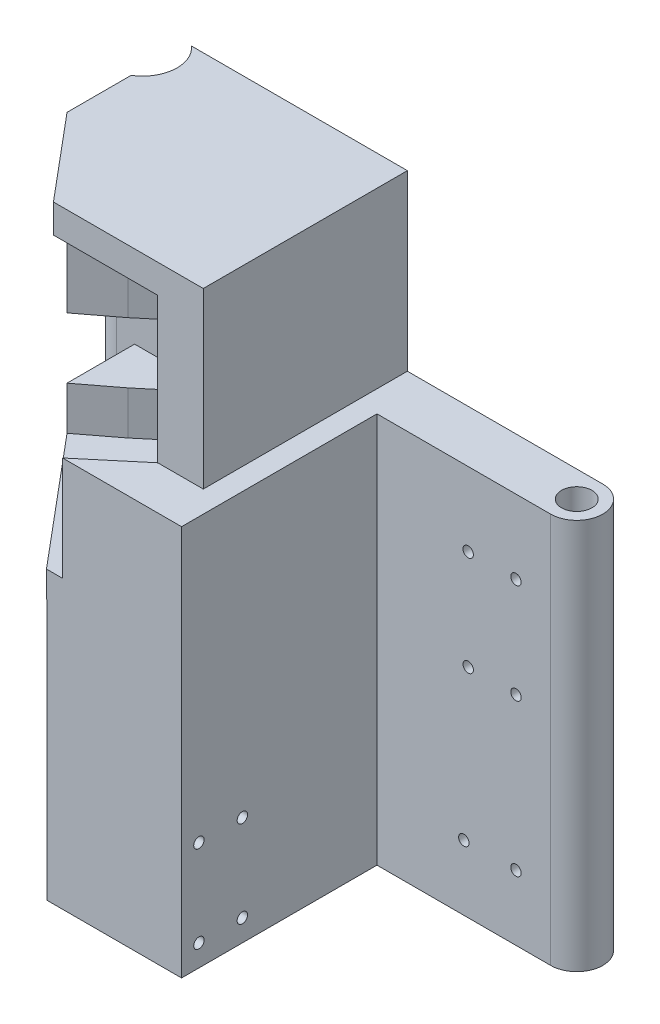
SolidWorks part; units mm, degrees
ref_plane "Front Plane" through (0, 0, 0) normal (0, 0, 1) x (1, 0, 0)
ref_plane "Top Plane" through (0, 0, 0) normal (0, 1, 0) x (1, 0, 0)
ref_plane "Right Plane" through (0, 0, 0) normal (1, 0, 0) x (0, 0, -1)
sketch "Sketch1" plane through (0, 0, 0) normal (0, 1, 0) x (1, 0, 0)
  line L0 (0, 7.62) -> (127, 7.62)
  line L1 (0, -7.62) -> (69.85, -7.62)
  line L2 (76.2, -7.62) -> (76.2, -64.77)
  line L3 (69.85, -7.62) -> (69.85, -64.77)
  line L4 (69.85, -64.77) -> (76.2, -64.77)
  line L5 (76.2, -7.62) -> (127, -7.62)
  circle A0 centre (0, 0) radius 4.445
  arc A1 (0, 7.62) -> (0, -7.62) centre (0, 0) ccw
  arc A2 (127, -7.62) -> (127, 7.62) centre (127, 0) ccw
  circle A3 centre (127, 0) radius 4.445
  dimension "D1" = 15.24
  dimension "D2" = 8.89
  dimension "D4" = 57.15
  dimension "D5" = 50.8
  dimension "D6" = 6.35
  dimension "D3" = 2
extrude "Boss-Extrude1" add sketch "Sketch1" along normal blind 114.3
sketch "Sketch5" plane through (76.2, 0, 0) normal (1, 0, 0) x (0, 0, -1)
sketch "Sketch12" plane through (0, 114.3, 0) normal (0, 1, 0) x (1, 0, 0)
  line L0 (69.85, -7.62) -> (69.85, -64.77)
  line L1 (69.85, -7.62) -> (69.85, -64.77) construction
  line L2 (69.85, -64.77) -> (21.8955, -7.62)
  line L3 (0, -7.62) -> (69.85, -7.62) construction
  line L4 (21.8955, -7.62) -> (69.85, -7.62)
  dimension "D1" = 40
  dimension "D2" = 57.15
extrude "Boss-Extrude3" add sketch "Sketch12" against normal blind 38.1
sketch "Sketch13" plane through (0, 114.3, 0) normal (0, 1, 0) x (1, 0, 0)
  line L0 (127, 7.62) -> (0, 7.62) construction
  line L1 (21.8955, -7.62) -> (69.85, -7.62)
  line L2 (21.8955, -7.62) -> (21.8955, 7.62)
  line L3 (21.8955, 7.62) -> (69.85, 7.62)
  line L4 (69.85, -7.62) -> (69.85, 7.62)
  line L5 (69.85, -7.62) -> (69.85, -64.77)
  line L6 (69.85, -64.77) -> (21.8955, -8.1167)
  line M7 (21.8955, -7.62) -> (69.85, -64.77)
  line M12 (127, 7.62) -> (0, 7.62)
  dimension "D1" = 90
extrude "Boss-Extrude4" add sketch "Sketch13" along normal blind 50.8 contours L1 L4 L2 M12 | L5 L1 M7
sketch "Sketch14" plane through (0, 76.2, 0) normal (0, -1, 0) x (1, 0, 0)
  line L0 (21.8955, 7.62) -> (69.85, 64.77)
  line L2 (12.1667, 15.7834) -> (53.2713, 64.77)
  line L3 (12.1667, 15.7834) -> (5.3168, 7.62)
  line L4 (0, 7.62) -> (69.85, 7.62) construction
  line L5 (69.85, 64.77) -> (53.2713, 64.77)
  line L6 (21.8955, 7.62) -> (5.3168, 7.62)
  line L7 (12.1667, 15.7834) -> (60.1212, 72.9334) construction
  dimension "D1" = 12.7
extrude "Boss-Extrude5" add sketch "Sketch14" against normal blind 7.62
sketch "Sketch15" plane through (0, 165.1, 0) normal (0, 1, 0) x (1, 0, 0)
  line L0 (69.85, -64.77) -> (53.2713, -64.77)
  line L1 (53.2713, -64.77) -> (5.3168, -7.62)
  line L2 (5.3168, -7.62) -> (5.3168, 7.62)
  line L3 (21.8955, 7.62) -> (0, 7.62) construction
  line L4 (5.3168, 7.62) -> (21.8955, 7.62)
  line L5 (21.8955, 7.62) -> (21.8955, -7.62)
  line L6 (21.8955, -7.62) -> (69.85, -64.77)
extrude "Boss-Extrude6" add sketch "Sketch15" against normal blind 8.382
sketch "Sketch17" plane through (0, 156.718, 0) normal (0, -1, 0) x (1, 0, 0)
  line L1 (5.3168, 7.62) -> (53.2713, 64.77) construction
  line L2 (12.1667, 15.7834) -> (5.3168, 7.62)
  line L3 (5.3168, 7.62) -> (5.3168, -7.62)
  line L4 (5.3168, -7.62) -> (21.8955, -7.62)
  line L5 (21.8955, -7.62) -> (21.8955, 7.62)
  line L6 (25.1608, 11.5115) -> (15.4321, 19.6749)
  line L7 (15.4321, 19.6749) -> (12.1667, 15.7834)
  line L8 (25.1608, 11.5115) -> (21.8955, 7.62)
  dimension "D1" = 5.08
extrude "Boss-Extrude7" add sketch "Sketch17" along normal blind 76.2
sketch "Sketch18" plane through (0, 76.2, 0) normal (0, -1, 0) x (1, 0, 0)
  line L0 (5.3168, 7.62) -> (5.3168, 27.3777)
  line L1 (5.3168, 7.62) -> (53.2713, 64.77)
  line L2 (5.3168, 27.3777) -> (36.6927, 64.77)
  line L3 (53.2713, 64.77) -> (36.6927, 64.77)
  line L5 (-4.412, 15.7834) -> (43.5426, 72.9334) construction
  dimension "D1" = 12.7
extrude "Boss-Extrude8" add sketch "Sketch18" against normal blind 7.62
sketch "Sketch19" plane through (0, 165.1, 0) normal (0, 1, 0) x (1, 0, 0)
  line L0 (5.3168, -7.62) -> (5.3168, -27.3777)
  line L1 (5.3168, -27.3777) -> (36.6927, -64.77)
  line L2 (36.6927, -64.77) -> (53.2713, -64.77)
  line L3 (69.85, -64.77) -> (36.6927, -64.77) construction
  line L4 (53.2713, -64.77) -> (5.3168, -7.62)
extrude "Boss-Extrude9" add sketch "Sketch19" against normal blind 8.382
sketch "Sketch20" plane through (0, 156.718, 0) normal (0, -1, 0) x (1, 0, 0)
  line L0 (15.4321, 19.6749) -> (5.3168, 27.3777)
  line L1 (5.3168, 27.3777) -> (5.3168, 7.62)
  line L2 (5.3168, 7.62) -> (15.4321, 19.6749)
extrude "Boss-Extrude10" add sketch "Sketch20" along normal blind 73.66
sketch "Sketch22" plane through (0, 156.718, 0) normal (0, -1, 0) x (1, 0, 0)
  line L0 (69.85, 64.77) -> (58.0947, 50.7606)
  line L1 (69.85, 64.77) -> (25.1608, 11.5115) construction
  line L2 (58.0947, 50.7606) -> (41.3989, 64.77)
  line L3 (36.6927, 64.77) -> (69.85, 64.77) construction
  line L4 (41.3989, 64.77) -> (69.85, 64.77)
  dimension "D1" = 18.288
extrude "Boss-Extrude11" add sketch "Sketch22" along normal blind 73.406
sketch "Sketch23" plane through (5.3168, 0, 0) normal (-1, 0, 0) x (0, 0, 1)
  line L5 (27.3777, 83.82) -> (27.3777, 156.718) construction
  line L6 (27.3777, 96.52) -> (7.62, 96.52)
  line L7 (27.3777, 96.52) -> (27.3777, 114.3)
  line L8 (27.3777, 114.3) -> (7.62, 114.3)
  line L9 (7.62, 96.52) -> (7.62, 114.3)
  line L10 (7.62, 114.3) -> (7.62, 76.2) construction
  dimension "D1" = 12.7
  dimension "D2" = 17.78
extrude "Cut-Extrude11" cut sketch "Sketch23" against normal blind 20.32
sketch "Sketch24" plane through (0, 165.1, 0) normal (0, 1, 0) x (1, 0, 0)
  circle A0 centre (0, 0) radius 10.16
  dimension "D1" = 20.32
extrude "Cut-Extrude12" cut sketch "Sketch24" against normal up to surface (50.8 mm away) up to face at (0, 114.3, 4.445)
sketch "Sketch25" plane through (0, 0, 64.77) normal (0, 0, 1) x (1, 0, 0)
  line L0 (5.3168, 156.718) -> (36.6927, 156.718) construction
  line L1 (69.85, 114.3) -> (36.6927, 114.3)
  line L2 (69.85, 114.3) -> (69.85, 165.1)
  line L3 (69.85, 165.1) -> (36.6927, 165.1)
  line L4 (36.6927, 114.3) -> (36.6927, 165.1)
  line L5 (36.6927, 165.1) -> (12.9618, 165.1)
  line L6 (36.6927, 165.1) -> (36.6927, 156.718)
  line L7 (36.6927, 156.718) -> (12.9618, 156.718)
  line L8 (12.9618, 165.1) -> (12.9618, 156.718)
  line M1 (41.3989, 156.718) -> (41.3989, 83.82)
  line M9 (69.85, 114.3) -> (69.85, 165.1)
  line M10 (69.85, 165.1) -> (36.6927, 165.1)
  line M11 (36.6927, 165.1) -> (36.6927, 156.718)
  line M12 (36.6927, 156.718) -> (41.3989, 156.718)
extrude "Cut-Extrude14" cut sketch "Sketch25" against normal blind 12.7 contours L1 M9 M10 M11 M12 M1 | L5 L8 L7 M11
sketch "Sketch26" plane through (0, 0, 7.62) normal (0, 0, 1) x (1, 0, 0)
  line L0 (69.85, 76.2) -> (5.3168, 76.2) construction
  line L1 (69.85, 0) -> (36.83, 0)
  line L2 (69.85, 0) -> (69.85, 76.2)
  line L3 (69.85, 76.2) -> (36.83, 76.2)
  line L4 (36.83, 0) -> (36.83, 76.2)
  dimension "D1" = 33.02
extrude "Boss-Extrude13" add sketch "Sketch26" along normal up to surface (57.15 mm away) up to face at (56.0354, 68.58, 64.77)
sketch "Sketch34" plane through (0, 0, -7.62) normal (0, 0, -1) x (-1, 0, 0)
  line L0 (-127, 114.3) -> (-69.85, 114.3) construction
  line L1 (-127, 114.3) -> (-127, 0) construction
  circle A0 centre (-109.22, 95.25) radius 1.524
  circle A1 centre (-95.25, 95.25) radius 1.524
  circle A2 centre (-95.25, 63.5) radius 1.524
  circle A3 centre (-109.22, 63.5) radius 1.524
  circle A10 centre (-109.22, 44.45) radius 1.524
  circle A11 centre (-95.25, 44.45) radius 1.524
  circle A12 centre (-109.22, 12.7) radius 1.524
  circle A13 centre (-95.25, 12.7) radius 1.524
  dimension "D1" = 3.048
  dimension "D2" = 2
  dimension "D5" = 13.97
  dimension "D6" = 31.75
  dimension "D7" = 13.97
  dimension "D8" = 19.05
  dimension "D9" = 17.78
extrude "Cut-Extrude18" cut sketch "Sketch34" against normal blind 5.08
sketch "Sketch35" plane through (0, 0, 7.62) normal (0, 0, 1) x (1, 0, 0)
  line L0 (127, 114.3) -> (127, 0) construction
  circle A4 centre (102.87, 92.71) radius 1.524
  circle A5 centre (116.84, 92.71) radius 1.524
  circle A6 centre (102.87, 63.5) radius 1.524
  circle A7 centre (116.84, 63.5) radius 1.524
  circle A8 centre (101.6, 19.05) radius 1.524
  circle A9 centre (116.84, 19.05) radius 1.524
  dimension "D1" = 3.048
  dimension "D2" = 3.048
  dimension "D3" = 44.45
  dimension "D4" = 1.27
  dimension "D5" = 29.21
  dimension "D6" = 13.97
  dimension "D7" = 13.97
  dimension "D8" = 10.16
  dimension "D9" = 2
extrude "Cut-Extrude19" cut sketch "Sketch35" against normal blind 5.08
sketch "Sketch36" plane through (76.2, 0, 0) normal (1, 0, 0) x (0, 0, -1)
  line L0 (-64.77, 114.3) -> (-64.77, 0) construction
  line L1 (-64.77, 0) -> (-7.62, 0) construction
  circle A0 centre (-59.69, 6.35) radius 1.524
  circle A1 centre (-46.99, 6.35) radius 1.524
  circle A2 centre (-46.99, 31.75) radius 1.524
  circle A3 centre (-59.69, 31.75) radius 1.524
  dimension "D1" = 3.048
  dimension "D2" = 5.08
  dimension "D3" = 6.35
extrude "Cut-Extrude20" cut sketch "Sketch36" against normal blind 5.08
sketch "Sketch37" plane through (0, 0, 0) normal (0, -1, 0) x (1, 0, 0)
  line L0 (0, 7.62) -> (36.83, 7.62) construction
  line L1 (46.99, 41.91) -> (68.58, 41.91)
  line L2 (46.99, 41.91) -> (46.99, 7.62)
  line L3 (46.99, 7.62) -> (68.58, 7.62)
  line L4 (68.58, 41.91) -> (68.58, 7.62)
  line L5 (76.2, 64.77) -> (76.2, 7.62) construction
  dimension "D1" = 21.59
  dimension "D2" = 34.29
  dimension "D3" = 7.62
extrude "Cut-Extrude21" cut sketch "Sketch37" against normal blind 50.8
sketch "Sketch38" plane through (0, 0, 0) normal (0, -1, 0) x (1, 0, 0)
  circle A0 centre (57.785, 48.26) radius 1.524
  circle A1 centre (57.785, 2.54) radius 1.524
  dimension "D4" = 3.048
  dimension "D1" = 6.35
  dimension "D2" = 10.795
  dimension "D3" = 2
extrude "Cut-Extrude22" cut sketch "Sketch38" against normal blind 10.16
sketch "Sketch39" plane through (0, 0, -7.62) normal (0, 0, -1) x (-1, 0, 0)
  line L0 (-127, 114.3) -> (-69.85, 114.3) construction
  line L1 (-69.85, 96.52) -> (-36.83, 96.52)
  line L2 (-69.85, 96.52) -> (-69.85, 45.72)
  line L3 (-69.85, 45.72) -> (-36.83, 45.72)
  line L4 (-36.83, 96.52) -> (-36.83, 45.72)
  line L5 (-69.85, 71.12) -> (-49.9261, 71.12)
  line L6 (-60.325, 96.52) -> (-53.975, 96.52)
  line L7 (-60.325, 96.52) -> (-60.325, 102.87)
  line L8 (-60.325, 102.87) -> (-53.975, 102.87)
  line L9 (-53.975, 96.52) -> (-53.975, 102.87)
  line L10 (-53.975, 45.72) -> (-53.975, 39.37)
  line L11 (-60.325, 39.37) -> (-53.975, 39.37)
  line L12 (-60.325, 45.72) -> (-60.325, 39.37)
  line L13 (-127, 114.3) -> (-127, 0) construction
  line L14 (-69.85, 67.945) -> (-76.2, 67.945)
  line L15 (-69.85, 67.945) -> (-69.85, 74.295)
  line L16 (-69.85, 74.295) -> (-76.2, 74.295)
  line L17 (-76.2, 67.945) -> (-76.2, 74.295)
  circle A0 centre (-57.15, 102.87) radius 3.175
  circle A1 centre (-57.15, 102.87) radius 1.27
  circle A2 centre (-57.15, 39.37) radius 1.27
  circle A3 centre (-57.15, 39.37) radius 3.175
  circle A4 centre (-76.2, 71.12) radius 3.175
  circle A5 centre (-76.2, 71.12) radius 1.27
  dimension "D5" = 6.35
  dimension "D7" = 2.54
  dimension "D9" = 6.35
  dimension "D10" = 2.54
  dimension "D1" = 50.8
  dimension "D2" = 33.02
  dimension "D3" = 17.78
  dimension "D4" = 6.35
  dimension "D6" = 9.525
  dimension "D8" = 6.35
  dimension "D11" = 22.225
  dimension "D12" = 57.15
extrude "Cut-Extrude23" cut sketch "Sketch39" against normal blind 5.08 contours L8 A1 | L8 A1 | A2 L11 | A2 L11 | L17 A5 | L17 A5
